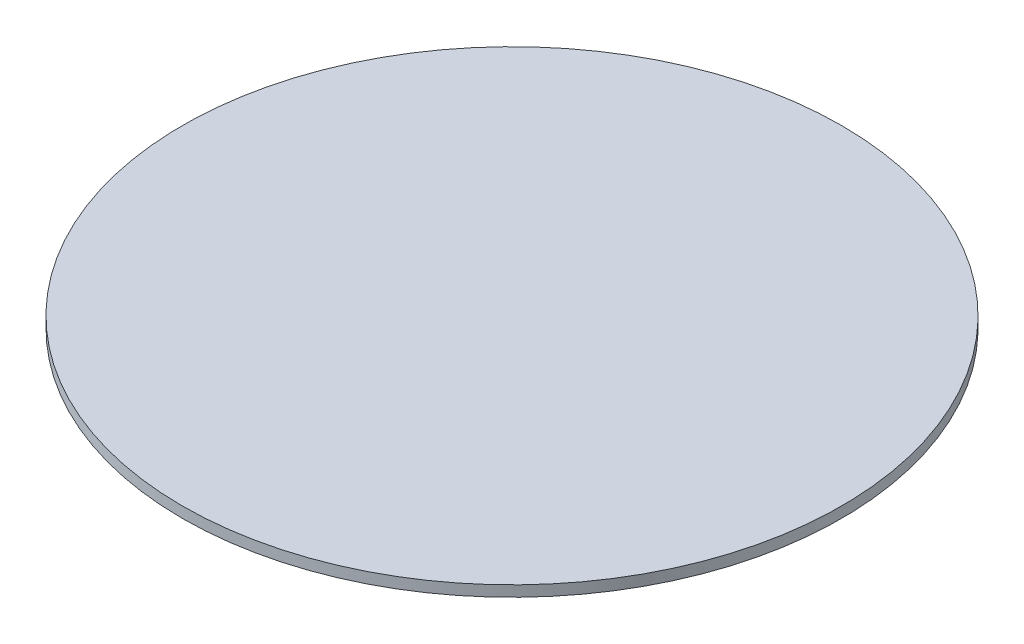
SolidWorks part; units mm, degrees
ref_plane "Front Plane" through (0, 0, 0) normal (0, 0, 1) x (1, 0, 0)
ref_plane "Top Plane" through (0, 0, 0) normal (0, 1, 0) x (1, 0, 0)
ref_plane "Right Plane" through (0, 0, 0) normal (1, 0, 0) x (0, 0, -1)
sketch "Sketch1" plane through (0, 0, 0) normal (0, 1, 0) x (1, 0, 0)
  circle A0 centre (0, 0) radius 305
  dimension "D1" = 610
extrude "Boss-Extrude1" add sketch "Sketch1" along normal blind 10
